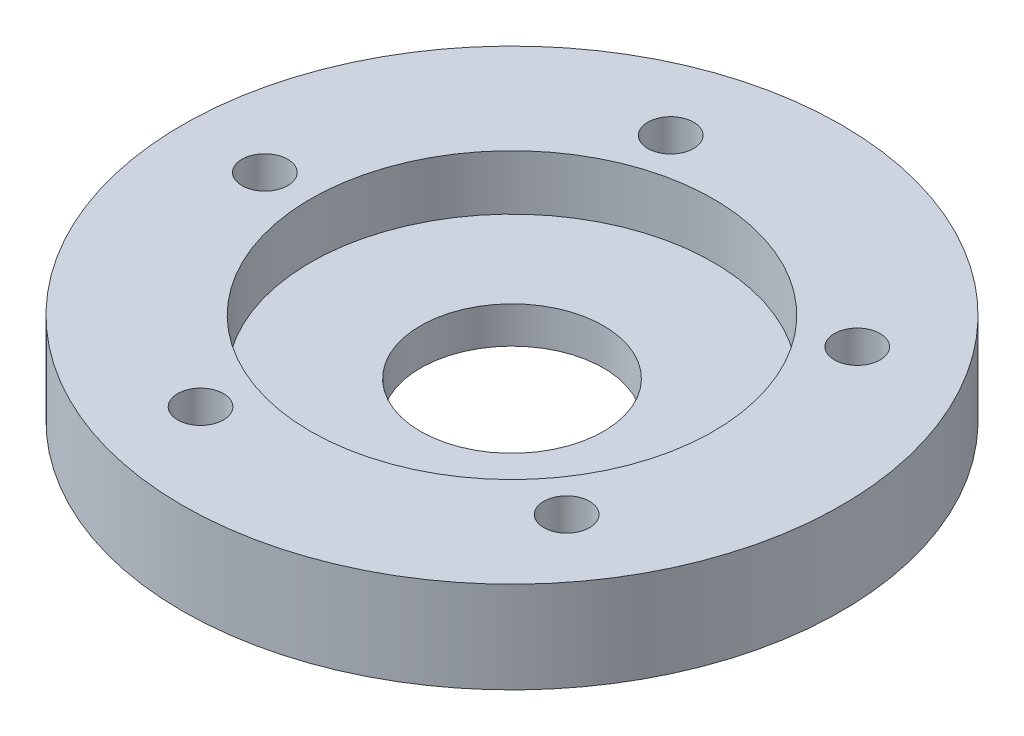
SolidWorks part; units mm, degrees
ref_plane "Front Plane" through (0, 0, 0) normal (0, 0, 1) x (1, 0, 0)
ref_plane "Top Plane" through (0, 0, 0) normal (0, 1, 0) x (1, 0, 0)
ref_plane "Right Plane" through (0, 0, 0) normal (1, 0, 0) x (0, 0, -1)
sketch "Sketch1" plane through (0, 0, 0) normal (0, 1, 0) x (1, 0, 0)
  line L0 (-13.5, 0) -> (13.5, 0) construction
  circle A0 centre (0, 0) radius 16
  circle A1 centre (0, 0) radius 13.5
  circle A2 centre (0, 0) radius 1.75
  circle A3 centre (-13.5, 0) radius 1.25
  circle A4 centre (-4.1717, 12.8393) radius 1.25
  circle A5 centre (10.9217, 7.9351) radius 1.25
  circle A6 centre (10.9217, -7.9351) radius 1.25
  circle A7 centre (-4.1717, -12.8393) radius 1.25
  point P19 (0, 0)
  dimension "D1" = 32
  dimension "D2" = 2.5
  dimension "D3" = 3.5
  dimension "D4" = 2.5
  dimension "D5" = 5
extrude "Boss-Extrude1" add sketch "Sketch1" along normal blind 2 and the other way blind 3 contours A0 A7 A1 A3 A4 A5 A6 | L0 A3 A1 A7 A6 A2 | A3 L0 A2 A1 A5 A4
sketch "Sketch2" plane through (0, 2, 0) normal (0, 1, 0) x (1, 0, 0)
  circle A0 centre (0, 0) radius 2.95
  circle A1 centre (0, 0) radius 4.95
  dimension "D1" = 5.9
  dimension "D2" = 2
extrude "Boss-Extrude3" add sketch "Sketch2" along normal blind 3 contours A1 A0
sketch "Sketch4" plane through (0, 2, 0) normal (0, 1, 0) x (1, 0, 0)
  circle A0 centre (0, 0) radius 2
sketch "Sketch5" plane through (0, -3, 0) normal (0, -1, 0) x (1, 0, 0)
  circle A0 centre (0, 0) radius 3.5
  dimension "D1" = 7
extrude "Cut-Extrude2" cut sketch "Sketch5" against normal blind 4
sketch "Sketch6" plane through (0, 2, 0) normal (0, 1, 0) x (1, 0, 0)
  circle A0 centre (0, 0) radius 16
  circle A1 centre (0, 0) radius 18
  dimension "D1" = 2
extrude "Boss-Extrude4" add sketch "Sketch6" against normal blind 5
sketch "Sketch7" plane through (0, 2, 0) normal (0, 1, 0) x (1, 0, 0)
  circle A0 centre (0, 0) radius 11
  dimension "22" = 22
extrude "Cut-Extrude3" cut sketch "Sketch7" against normal blind 3 and the other way blind 10
sketch "Sketch8" plane through (0, -1, 0) normal (0, 1, 0) x (1, 0, 0)
  circle A0 centre (0, 0) radius 5
  dimension "D1" = 10
extrude "Cut-Extrude4" cut sketch "Sketch8" against normal blind 3
